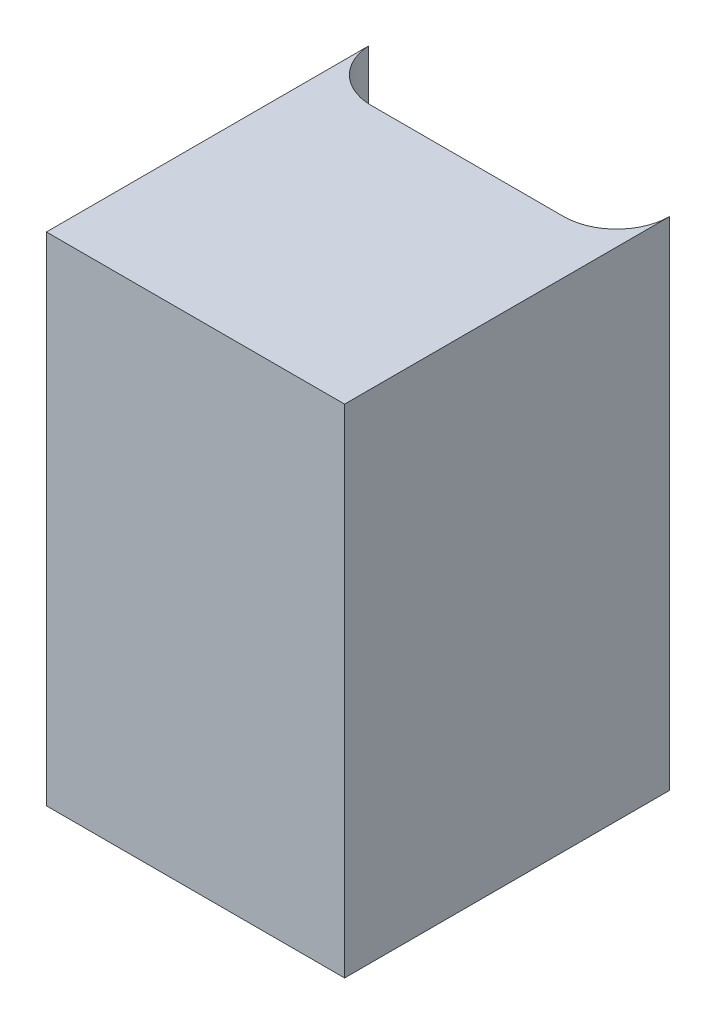
SolidWorks part; units mm, degrees
ref_plane "Спереди" through (0, 0, 0) normal (0, 0, 1) x (1, 0, 0)
ref_plane "Сверху" through (0, 0, 0) normal (0, 1, 0) x (1, 0, 0)
ref_plane "Справа" through (0, 0, 0) normal (1, 0, 0) x (0, 0, -1)
sketch "Эскиз1" plane through (0, 0, 0) normal (1, 0, 0) x (0, 0, -1)
  line L1 (0, 8.2506) -> (-20, 8.2506)
  line L2 (0, 8.2506) -> (0, -21.7494)
  line L3 (0, -21.7494) -> (-20, -21.7494)
  line L4 (-20, 8.2506) -> (-20, -21.7494)
extrude "Вытянуть1" add sketch "Эскиз1" along normal blind 18
sketch "Эскиз2" plane through (0, 8.2506, 0) normal (0, 1, 0) x (1, 0, 0)
  line L0 (18, 0) -> (18, -20) construction
  line L1 (-0.0049, 0.1468) -> (18, 0.1468)
  line L2 (-0.0049, 0.1468) -> (-0.0049, -0.3822)
  line L3 (3.1951, -3.5822) -> (14.8, -3.5822)
  line L4 (18, 0.1468) -> (18, -0.3822)
  arc A0 (14.8, -3.5822) -> (18, -0.3822) centre (14.8, -0.3822) ccw
  arc A1 (-0.0049, -0.3822) -> (3.1951, -3.5822) centre (3.1951, -0.3822) ccw
  point P9 (18, -3.5822)
  dimension "D1" = 3.2
extrude "Вырез-Вытянуть4" cut sketch "Эскиз2" against normal through all
